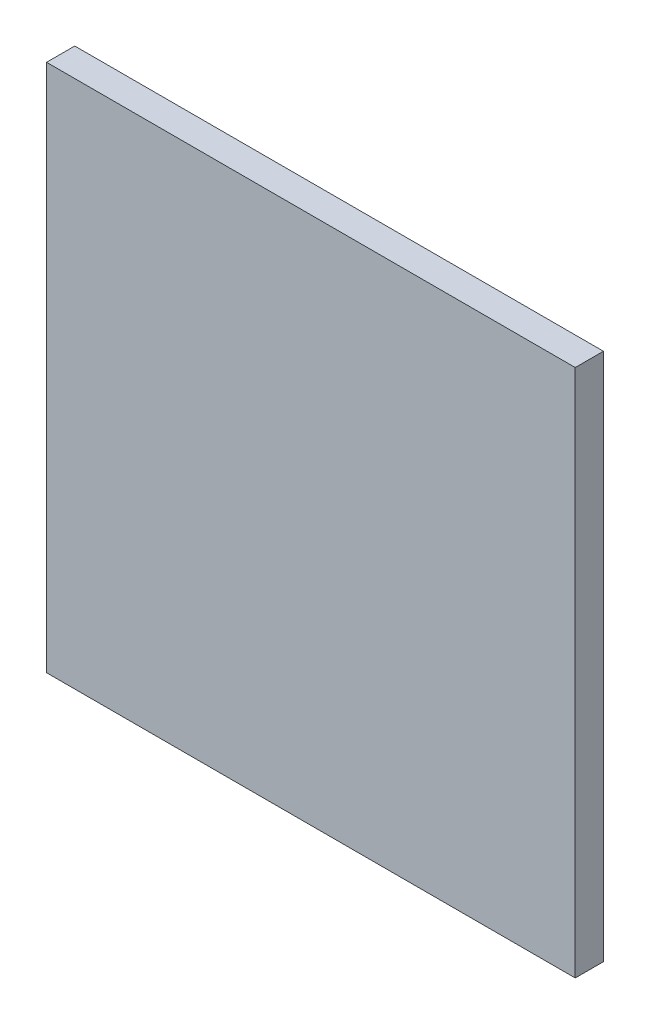
SolidWorks part; units mm, degrees
material "Glass"
ref_plane "Front Plane" through (0, 0, 0) normal (0, 0, 1) x (1, 0, 0)
ref_plane "Top Plane" through (0, 0, 0) normal (0, 1, 0) x (1, 0, 0)
ref_plane "Right Plane" through (0, 0, 0) normal (1, 0, 0) x (0, 0, -1)
sketch "Sketch1" plane through (0, 0, 0) normal (0, 0, 1) x (1, 0, 0)
  line L1 (44.3929, 35.4949) -> (120.5929, 35.4949)
  line L2 (44.3929, 35.4949) -> (44.3929, -40.7051)
  line L3 (44.3929, -40.7051) -> (120.5929, -40.7051)
  line L4 (120.5929, 35.4949) -> (120.5929, -40.7051)
  dimension "D1" = 76.2
  dimension "D2" = 76.2
extrude "Boss-Extrude1" add sketch "Sketch1" along normal blind 4.064
